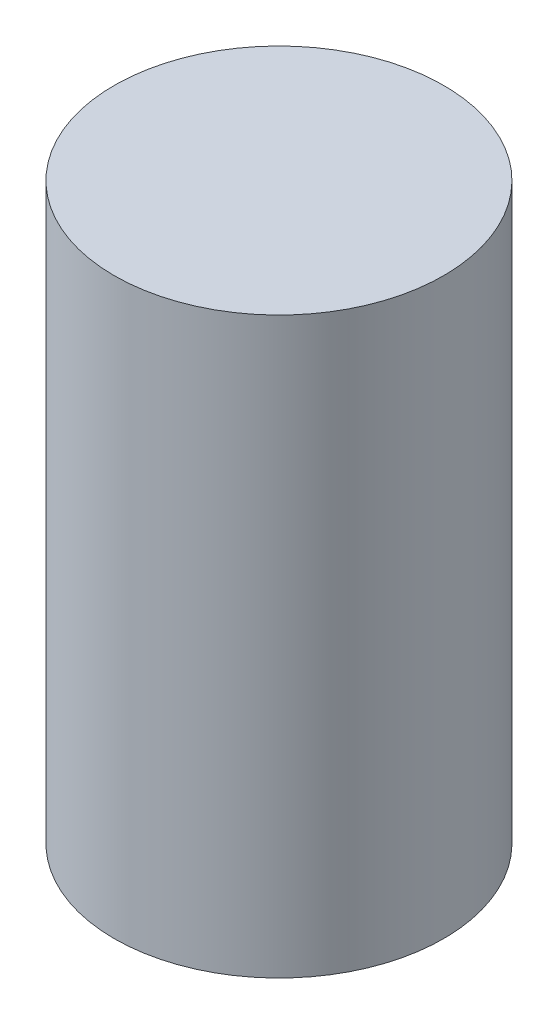
SolidWorks part; units mm, degrees
ref_plane "Front Plane" through (0, 0, 0) normal (0, 0, 1) x (1, 0, 0)
ref_plane "Top Plane" through (0, 0, 0) normal (0, 1, 0) x (1, 0, 0)
ref_plane "Right Plane" through (0, 0, 0) normal (1, 0, 0) x (0, 0, -1)
sketch "Sketch1" plane through (0, 0, 0) normal (0, 1, 0) x (1, 0, 0)
  circle A0 centre (0, 0) radius 6.6
  dimension "D1" = 13.2
extrude "Boss-Extrude1" add sketch "Sketch1" along normal blind 23 contours A0
